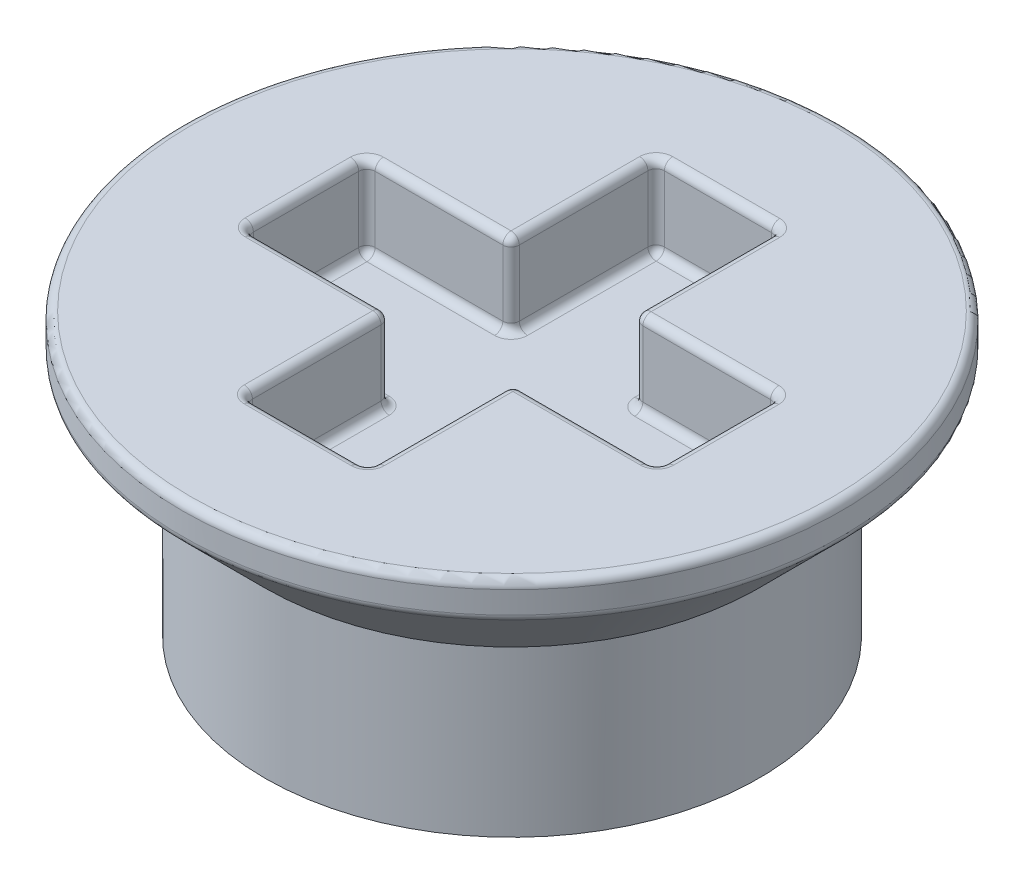
SolidWorks part; units mm, degrees
material "moto_black"
ref_plane "Front Plane" through (0, 0, 0) normal (0, 0, 1) x (1, 0, 0)
ref_plane "Top Plane" through (0, 0, 0) normal (0, 1, 0) x (1, 0, 0)
ref_plane "Right Plane" through (0, 0, 0) normal (1, 0, 0) x (0, 0, -1)
sketch "Sketch1" plane through (0, 0, 0) normal (0, 1, 0) x (1, 0, 0)
  circle A0 centre (0, 0) radius 4
  dimension "D1" = 8
extrude "Boss-Extrude1" add sketch "Sketch1" along normal blind 1.41
chamfer "Chamfer2" distance 1 angle 45 1 edges at (0, 0, 4)
sketch "Sketch2" plane through (0, 0, 0) normal (0, -1, 0) x (1, 0, 0)
  circle A2 centre (0, 0) radius 3
  circle A3 centre (0, 0) radius 3
  dimension "D1" = 0
extrude "Boss-Extrude2" add sketch "Sketch2" along normal blind 2
sketch "Sketch4" plane through (0, 1.41, 0) normal (0, 1, 0) x (1, 0, 0)
  line L1 (-0.75, -2.5) -> (0.75, -2.5)
  line L2 (-0.75, -2.5) -> (-0.75, 2.5)
  line L3 (-0.75, 2.5) -> (0.75, 2.5)
  line L4 (0.75, -2.5) -> (0.75, 2.5)
  line L5 (-0.75, -2.5) -> (0.75, 2.5) construction
  line L6 (-0.75, 2.5) -> (0.75, -2.5) construction
  line L7 (-2.5, -0.7389) -> (2.5, -0.7389)
  line L8 (-2.5, -0.7389) -> (-2.5, 0.7389)
  line L9 (-2.5, 0.7389) -> (2.5, 0.7389)
  line L10 (2.5, -0.7389) -> (2.5, 0.7389)
  line L11 (-2.5, -0.7389) -> (2.5, 0.7389) construction
  line L12 (-2.5, 0.7389) -> (2.5, -0.7389) construction
  point P0 (0, 0)
  point P6 (0, 0)
  dimension "D1" = 1.5
  dimension "D2" = 5
  dimension "D3" = 1.4779
  dimension "D4" = 5
extrude "Cut-Extrude1" cut sketch "Sketch4" against normal blind 1 contours L2 L9 L4 L3 | L9 L2 L7 L4 | L7 L2 L1 L4 | L9 L8 L7 L2 | L7 L10 L9 L4
fillet "Fillet2" radius 0.1 37 edges at (-2.5, 0.91, -0.7389) (-0.75, 0.91, -2.5) (-0.75, 0.91, -0.7389) (-2.5, 1.41, 0) (0, 1.41, 2.5) (0, 1.41, -2.5) (-0.75, 1.41, -1.6195) (-1.625, 1.41, -0.7389) (0, 1.41, 4) (0, 0.41, -2.5) (0, 0.41, 2.5) (-2.5, 0.41, 0) (-1.625, 0.41, -0.7389) (-0.75, 0.41, -1.6195) (-2.5, 0.91, 0.7389) (-1.625, 1.41, 0.7389) (-1.625, 0.41, 0.7389) (-0.75, 0.91, 0.7389) (-0.75, 1.41, 1.6195) (-0.75, 0.41, 1.6195) (-0.75, 0.91, 2.5) (1.625, 1.41, 0.7389) (1.625, 0.41, 0.7389) (0.75, 0.91, 2.5) (0.75, 1.41, 1.6195) (0.75, 0.41, 1.6195) (0.75, 0.91, 0.7389) (2.5, 0.91, 0.7389) (2.5, 1.41, 0) (2.5, 0.41, 0) (2.5, 0.91, -0.7389) (1.625, 1.41, -0.7389) (1.625, 0.41, -0.7389) (0.75, 0.91, -0.7389) (0.75, 1.41, -1.6195) (0.75, 0.41, -1.6195) (0.75, 0.91, -2.5)
fillet "Fillet3" radius 0.1 1 edges at (0, 1, 4)
